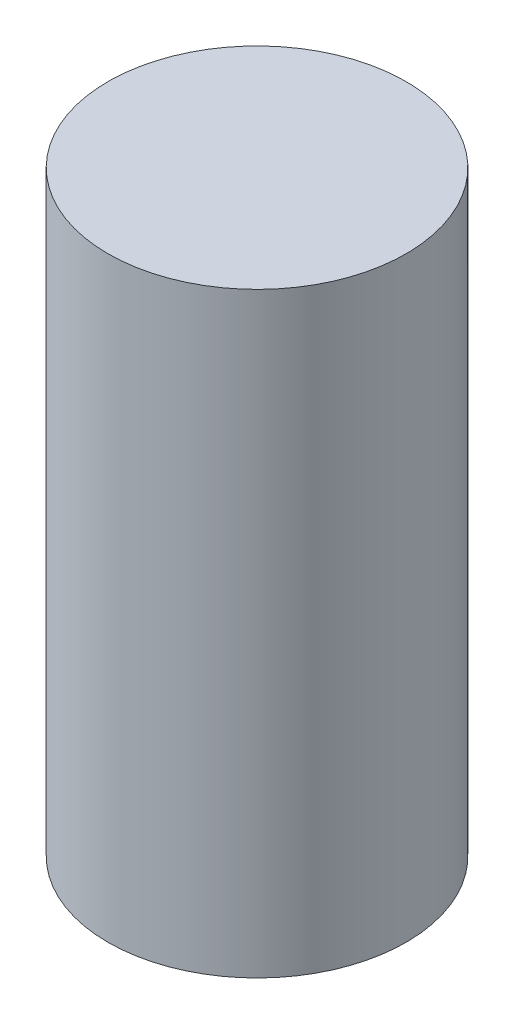
SolidWorks part; units mm, degrees
ref_plane "前视基准面" through (0, 0, 0) normal (0, 0, 1) x (1, 0, 0)
ref_plane "上视基准面" through (0, 0, 0) normal (0, 1, 0) x (1, 0, 0)
ref_plane "右视基准面" through (0, 0, 0) normal (1, 0, 0) x (0, 0, -1)
other "Configuration Table"
sketch "草图1" plane through (0, 0, 0) normal (0, 1, 0) x (1, 0, 0)
  circle A0 centre (0, 0) radius 100
  dimension "D1" = 200
extrude "凸台-拉伸1" add sketch "草图1" along normal blind 400
